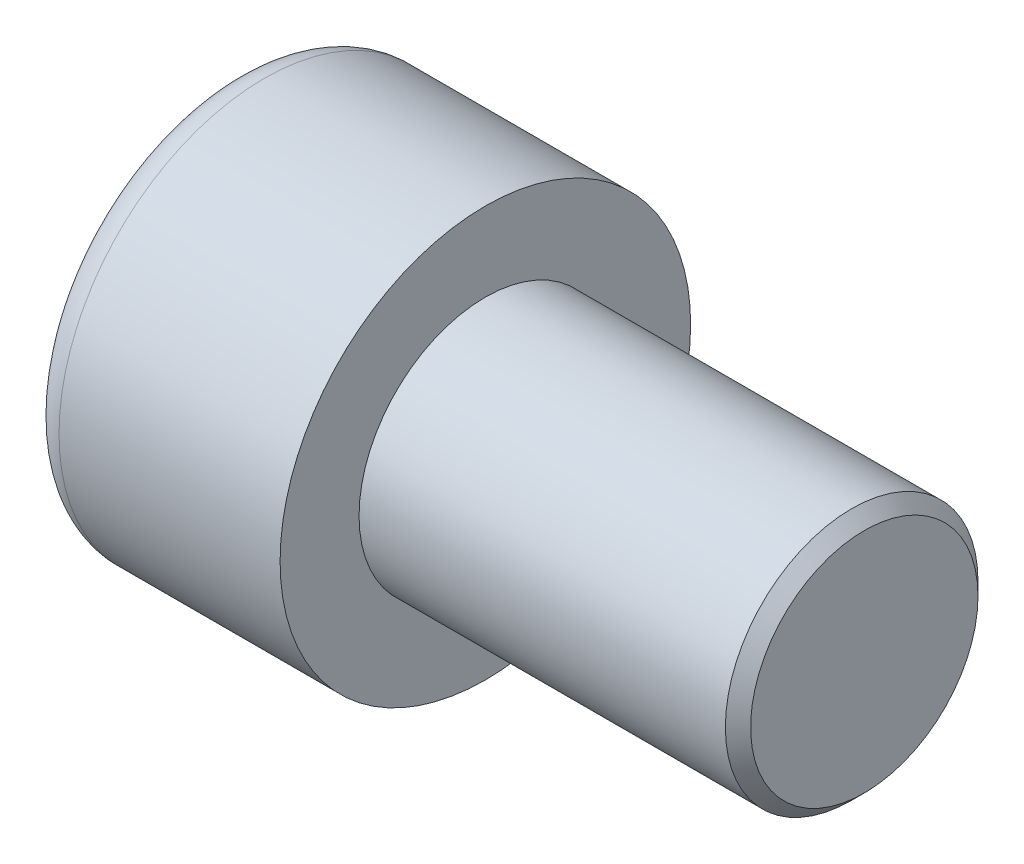
SolidWorks part; units mm, degrees
ref_plane "Front" through (0, 0, 0) normal (0, 0, 1) x (1, 0, 0)
ref_plane "Top" through (0, 0, 0) normal (0, 1, 0) x (1, 0, 0)
ref_plane "Right" through (0, 0, 0) normal (1, 0, 0) x (0, 0, -1)
sketch "Sketch1" plane through (0, 0, 0) normal (1, 0, 0) x (0, 0, -1)
  circle A0 centre (0, 0) radius 6.5
  dimension "dk" = 13
extrude "BaseHead" add sketch "Sketch1" along normal blind 8
sketch "Sketch2" plane through (8, 0, 0) normal (1, 0, 0) x (0, 0, -1)
  circle A0 centre (0, 0) radius 4
  dimension "d" = 8
extrude "BaseBody" add sketch "Sketch2" along normal blind 12
cosmetic thread "ThreadCosmetic1" [suppressed] parameters "b"=12, "D2"=6.647
sketch "Sketch3" plane through (0, 0, 0) normal (1, 0, 0) x (0, 0, -1)
  line L1 (3.4641, 0) -> (1.7321, 3)
  line L2 (1.7321, 3) -> (-1.7321, 3)
  line L3 (-1.7321, 3) -> (-3.4641, 0)
  line L4 (-3.4641, 0) -> (-1.7321, -3)
  line L5 (-1.7321, -3) -> (1.7321, -3)
  line L6 (1.7321, -3) -> (3.4641, 0)
  circle A0 centre (0, 0) radius 3 construction
  dimension "s" = 6
  dimension "e" = 6.9282
extrude "HexagonSocket" cut sketch "Sketch3" along normal blind 4
sketch "Sketch4" plane through (-4.1961, 0.75, 0) normal (0, 0, 1) x (-1, 0, 0)
  line L0 (-8.1961, 3.75) -> (-9.9282, 0.75)
  line L2 (-9.9282, 0.75) -> (-8.1961, 0.75)
  line L3 (-8.1961, 0.75) -> (-8.1961, 3.75)
  line L4 (-5.0351, 0.75) -> (0.839, 0.75) construction
  line L5 (-24.1961, 0.75) -> (-12.1961, 0.75) construction
  line L6 (-12.1961, 0.75) -> (-4.1961, 0.75) construction
  dimension "m" = 60
revolve "Cut-Revolve1" cut sketch "Sketch4" angle 360 about L4
fillet "HeadFillet" [suppressed] radius 0.4
fillet "TopFillet" radius 1 1 edges at (0, 0, -6.5)
chamfer "Chamfer1" distance 0.4 angle 45 1 edges at (20, 0, -4)
sketch "Sketch5" plane through (0, 0, 0) normal (0, 0, 1) x (1, 0, 0)
  line L0 (19.6, 3.4141) -> (19.9382, 4)
  line L1 (19.9382, 4) -> (19.9382, 4.6765)
  line L2 (19.9382, 4.6765) -> (19.2618, 4.6765)
  line L3 (19.2618, 4.6765) -> (19.2618, 4)
  line L4 (19.2618, 4) -> (19.6, 3.4141)
  line L5 (0, 0) -> (7.8886, 0) construction
  line L6 (19.6, -4) -> (19.6, 4) construction
  dimension "D1" = 8
  dimension "D2" = 0.6765
revolve "Cut-Revolve10" [suppressed] cut sketch "Sketch5" angle 360 about L5
pattern_linear "LPattern10" [suppressed] count 15 spacing 0.8118 along (1, 0, 0)
equation "\"r1@TopFillet\" = \"d@Sketch2\" / 8"
equation "\"D1@Chamfer1\" = \"r@HeadFillet\""
equation "\"D1@Sketch5\" = \"d@Sketch2\""
equation "\"D2@Sketch5\" =  ( \"d@Sketch2\" - \"D2@ThreadCosmetic1\" )  / 2"
equation "\"D3@LPattern10\" = \"D2@Sketch5\" * 1.2"
equation "\"D1@LPattern10\" = \"b@ThreadCosmetic1\" / \"D3@LPattern10\""
